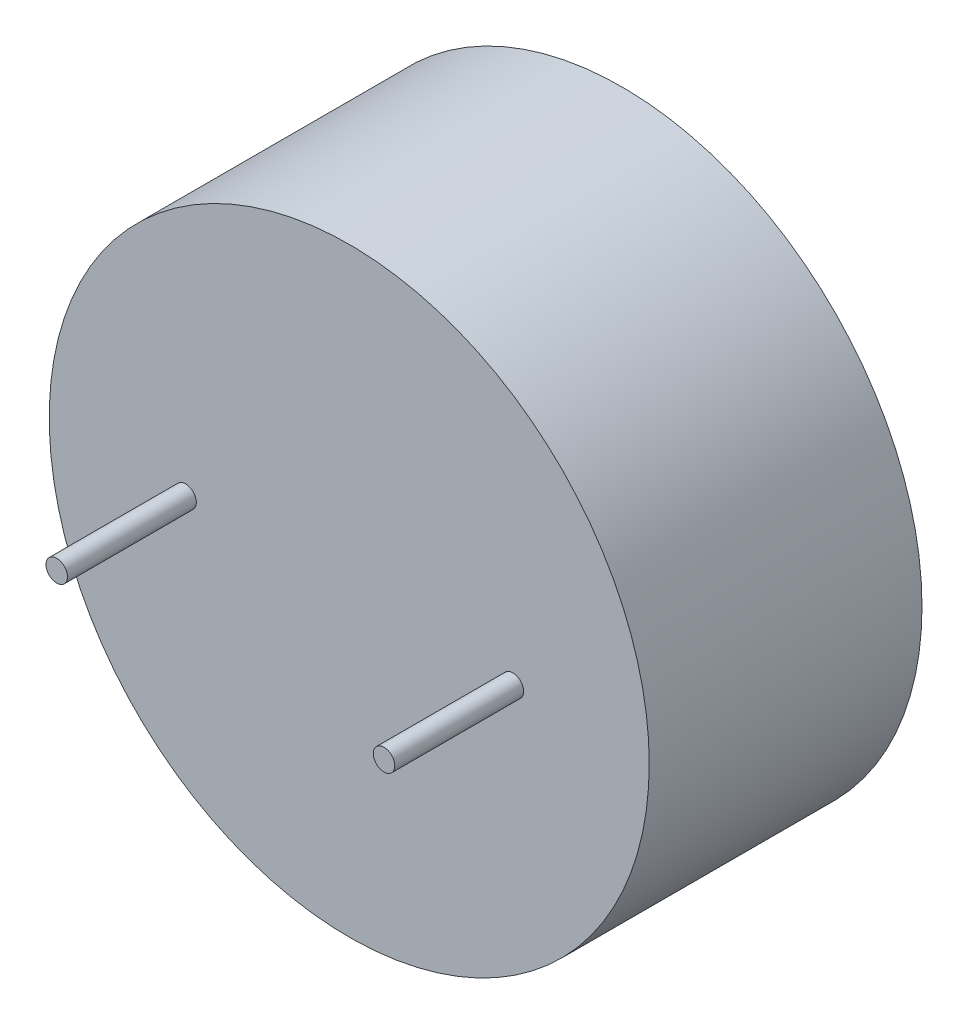
SolidWorks part; units mm, degrees
ref_plane "Front Plane" through (0, 0, 0) normal (0, 0, 1) x (1, 0, 0)
ref_plane "Top Plane" through (0, 0, 0) normal (0, 1, 0) x (1, 0, 0)
ref_plane "Right Plane" through (0, 0, 0) normal (1, 0, 0) x (0, 0, -1)
sketch "Sketch1" plane through (0, 0, 0) normal (0, 0, 1) x (1, 0, 0)
  circle A0 centre (0, 0) radius 13.97
  dimension "D1" = 27.94
extrude "Boss-Extrude1" add sketch "Sketch1" along normal blind 12.7
sketch "Sketch2" plane through (0, 0, 12.7) normal (0, 0, 1) x (1, 0, 0)
  circle A0 centre (-7.62, 0) radius 0.5
  circle A1 centre (7.62, 0) radius 0.5
  circle A2 centre (0, 0) radius 13.97 construction
  dimension "D1" = 1
  dimension "D2" = 1
  dimension "D3" = 15.24
  dimension "D4" = 7.62
extrude "Boss-Extrude2" add sketch "Sketch2" along normal blind 6
